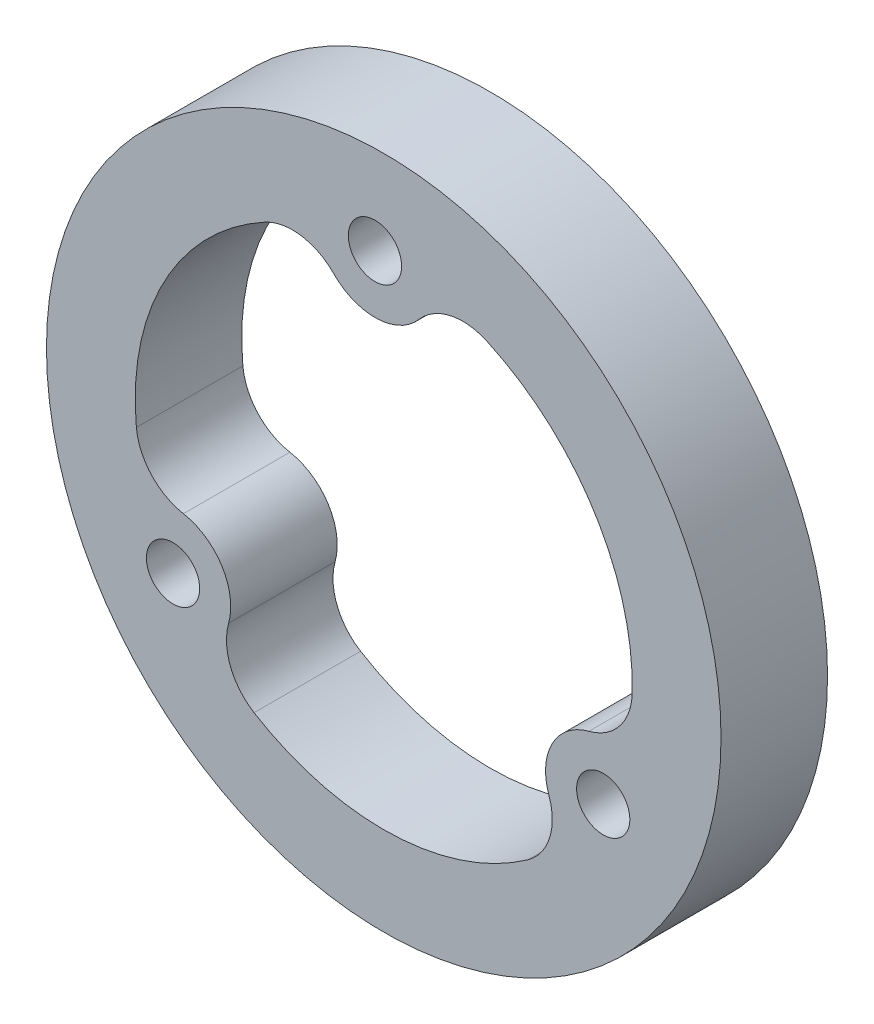
SolidWorks part; units mm, degrees
ref_plane "Plan de face" through (0, 0, 0) normal (0, 0, 1) x (1, 0, 0)
ref_plane "Plan de dessus" through (0, 0, 0) normal (0, 1, 0) x (1, 0, 0)
ref_plane "Plan de droite" through (0, 0, 0) normal (1, 0, 0) x (0, 0, -1)
sketch "Esquisse1" plane through (0, 0, 0) normal (0, 0, 1) x (1, 0, 0)
  line L0 (-0.4938, 13.9913) -> (-11.8699, -7.4233) construction
  line L1 (-11.8699, -7.4233) -> (12.3637, -6.568) construction
  line L2 (12.3637, -6.568) -> (-0.4938, 13.9913) construction
  circle A0 centre (0, 0) radius 19
  circle A2 centre (-0.4938, 13.9913) radius 1.5
  arc A12 (-2.8156, 11.7171) -> (1.9825, 11.8865) centre (-0.4938, 13.9913) ccw
  arc A16 (5.8069, 12.7389) -> (1.9825, 11.8865) centre (4.4589, 9.7817) ccw
  arc A17 (-2.8156, 11.7171) -> (-6.6905, 12.2978) centre (-5.1374, 9.443) ccw
  arc A18 (-6.6905, 12.2978) -> (-13.9357, -1.3405) centre (0, 0) ccw
  arc A19 (8.1288, -11.3984) -> (9.3027, -7.6602) centre (6.2417, -8.7523) ccw
  arc A20 (11.5551, -3.4202) -> (9.3027, -7.6602) centre (12.3637, -6.568) ccw
  arc A21 (11.5551, -3.4202) -> (13.9955, -0.3547) centre (10.7465, -0.2724) ccw
  circle A22 centre (12.3637, -6.568) radius 1.5
  arc A23 (-13.9357, -1.3405) -> (-11.2853, -4.2263) centre (-10.7006, -1.0293) ccw
  arc A24 (-8.7395, -8.2969) -> (-11.2853, -4.2263) centre (-11.8699, -7.4233) ccw
  arc A25 (-8.7395, -8.2969) -> (-7.305, -11.9431) centre (-5.6092, -9.1706) ccw
  circle A26 centre (-11.8699, -7.4233) radius 1.5
  arc A27 (-7.305, -11.9431) -> (8.1288, -11.3984) centre (0, 0) ccw
  arc A28 (13.9955, -0.3547) -> (5.8069, 12.7389) centre (0, 0) ccw
  circle A29 centre (-0.4938, 13.9913) radius 3.25 construction
  point P31 (0, 0)
  dimension "D1" = 38
  dimension "D2" = 3
  dimension "D3" = 3
  dimension "D4" = 6.5
  dimension "D10" = 14
  dimension "D6" = 60
  dimension "D7" = 60
extrude "Boss.-Extru.2" add sketch "Esquisse1" along normal blind 6
